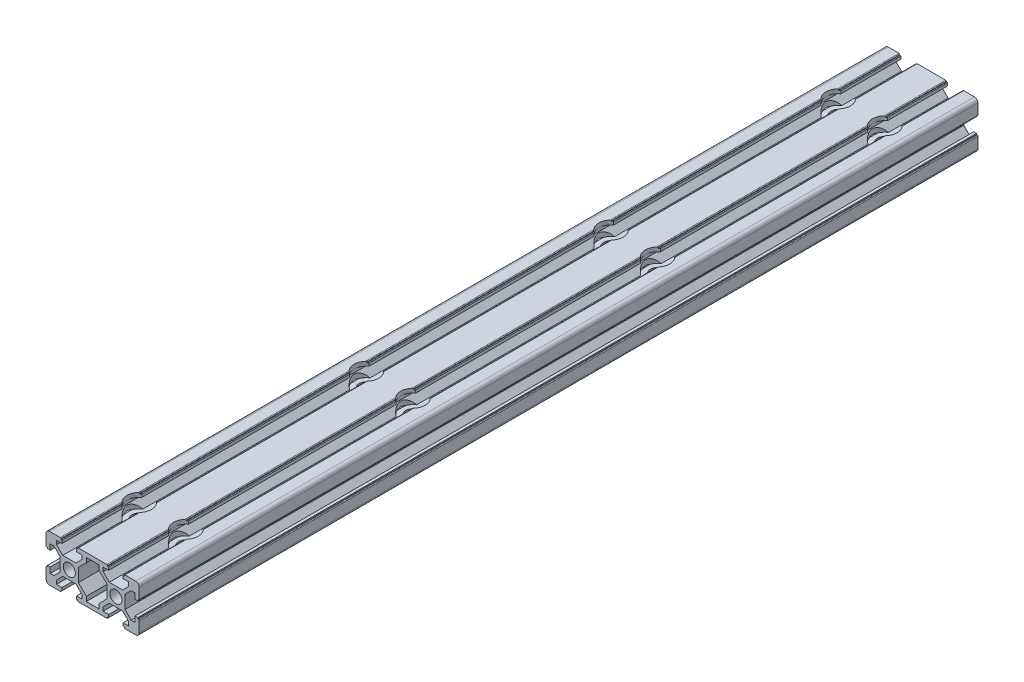
SolidWorks part; units mm, degrees
ref_plane "前视基准面" through (0, 0, 0) normal (0, 0, 1) x (1, 0, 0)
ref_plane "上视基准面" through (0, 0, 0) normal (0, 1, 0) x (1, 0, 0)
ref_plane "右视基准面" through (0, 0, 0) normal (1, 0, 0) x (0, 0, -1)
sketch "草图1" plane through (0, 0, 0) normal (0, 0, 1) x (1, 0, 0)
  line L0 (0, 0) -> (0, -41497.3383) construction
  line L1 (0, 0) -> (41497.3383, 0) construction
  line L2 (-13.9, 0) -> (-13.9, 2.8393)
  line L3 (-13.9, 2.8393) -> (-16.5607, 5.5)
  line L4 (-16.5607, 5.5) -> (-18.2, 5.5)
  line L5 (-18.2, 5.5) -> (-18.2, 3.1)
  line L6 (-18.2, 3.1) -> (-19.4, 3.1)
  line L7 (-19.4, 3.1) -> (-19.4, 3.6)
  line L8 (-19.4, 3.6) -> (-20, 3.6)
  line L9 (-20, 3.6) -> (-20, 10)
  line L10 (-20, 10) -> (-13.6, 10)
  line L11 (-13.6, 10) -> (-13.6, 9.4)
  line L12 (-13.6, 9.4) -> (-13.1, 9.4)
  line L13 (-13.1, 9.4) -> (-13.1, 8.2)
  line L14 (-13.1, 8.2) -> (-15.5, 8.2)
  line L15 (-15.5, 6.5607) -> (-12.8393, 3.9)
  line L16 (-12.8393, 3.9) -> (-7.1607, 3.9)
  line L17 (-4.5, 6.5607) -> (-7.1607, 3.9)
  line L18 (-4.5, 6.5607) -> (-4.5, 8.2)
  line L19 (-4.5, 8.2) -> (-6.9, 8.2)
  line L20 (-6.9, 8.2) -> (-6.9, 9.4)
  line L21 (-6.9, 9.4) -> (-6.4, 9.4)
  line L22 (-6.4, 9.4) -> (-6.4, 10)
  line L23 (-6.4, 10) -> (6.4, 10)
  line L24 (-15.5, 8.2) -> (-15.5, 6.5607)
  line L25 (-10, 0) -> (-20, 10) construction
  line L26 (-6.1, -2.8393) -> (-6.1, 2.8393)
  line L27 (-6.1, 2.8393) -> (-2.7, 6.2393)
  line L28 (-2.7, 6.2393) -> (-2.7, 8.2)
  line L29 (-2.7, 8.2) -> (2.7, 8.2)
  line L30 (-10, 0) -> (0, 10) construction
  line L31 (13.9, 0) -> (13.9, 2.8393)
  line L32 (6.1, -2.8393) -> (6.1, 2.8393)
  line L33 (4.5, 6.5607) -> (7.1607, 3.9)
  line L34 (12.8393, 3.9) -> (7.1607, 3.9)
  line L35 (6.1, 2.8393) -> (2.7, 6.2393)
  line L36 (2.7, 6.2393) -> (2.7, 8.2)
  line L37 (4.5, 6.5607) -> (4.5, 8.2)
  line L38 (6.4, 9.4) -> (6.4, 10)
  line L39 (6.9, 9.4) -> (6.4, 9.4)
  line L40 (6.9, 8.2) -> (6.9, 9.4)
  line L41 (4.5, 8.2) -> (6.9, 8.2)
  line L42 (13.1, 9.4) -> (13.1, 8.2)
  line L43 (13.6, 9.4) -> (13.1, 9.4)
  line L44 (13.6, 10) -> (13.6, 9.4)
  line L45 (20, 10) -> (13.6, 10)
  line L46 (20, 3.6) -> (20, 10)
  line L47 (19.4, 3.6) -> (20, 3.6)
  line L48 (19.4, 3.1) -> (19.4, 3.6)
  line L49 (18.2, 3.1) -> (19.4, 3.1)
  line L50 (18.2, 5.5) -> (18.2, 3.1)
  line L51 (16.5607, 5.5) -> (18.2, 5.5)
  line L52 (13.9, 2.8393) -> (16.5607, 5.5)
  line L53 (15.5, 6.5607) -> (12.8393, 3.9)
  line L54 (15.5, 8.2) -> (15.5, 6.5607)
  line L55 (13.1, 8.2) -> (15.5, 8.2)
  line L56 (15.5, -6.5607) -> (12.8393, -3.9)
  line L57 (13.9, -2.8393) -> (16.5607, -5.5)
  line L58 (16.5607, -5.5) -> (18.2, -5.5)
  line L59 (18.2, -5.5) -> (18.2, -3.1)
  line L60 (18.2, -3.1) -> (19.4, -3.1)
  line L61 (19.4, -3.1) -> (19.4, -3.6)
  line L62 (19.4, -3.6) -> (20, -3.6)
  line L63 (12.8393, -3.9) -> (7.1607, -3.9)
  line L64 (13.9, 0) -> (13.9, -2.8393)
  line L65 (13.1, -8.2) -> (15.5, -8.2)
  line L66 (15.5, -8.2) -> (15.5, -6.5607)
  line L67 (20, -3.6) -> (20, -10)
  line L68 (20, -10) -> (13.6, -10)
  line L69 (13.6, -10) -> (13.6, -9.4)
  line L70 (13.6, -9.4) -> (13.1, -9.4)
  line L71 (13.1, -9.4) -> (13.1, -8.2)
  line L72 (4.5, -8.2) -> (6.9, -8.2)
  line L73 (6.9, -8.2) -> (6.9, -9.4)
  line L74 (6.9, -9.4) -> (6.4, -9.4)
  line L75 (6.4, -9.4) -> (6.4, -10)
  line L76 (4.5, -6.5607) -> (4.5, -8.2)
  line L77 (2.7, -6.2393) -> (2.7, -8.2)
  line L78 (6.1, -2.8393) -> (2.7, -6.2393)
  line L79 (4.5, -6.5607) -> (7.1607, -3.9)
  line L80 (-2.7, -8.2) -> (2.7, -8.2)
  line L81 (-2.7, -6.2393) -> (-2.7, -8.2)
  line L82 (-6.1, -2.8393) -> (-2.7, -6.2393)
  line L83 (-4.5, -6.5607) -> (-7.1607, -3.9)
  line L84 (-4.5, -8.2) -> (-6.9, -8.2)
  line L85 (-4.5, -6.5607) -> (-4.5, -8.2)
  line L86 (-6.4, -10) -> (6.4, -10)
  line L87 (-6.4, -9.4) -> (-6.4, -10)
  line L88 (-6.9, -9.4) -> (-6.4, -9.4)
  line L89 (-6.9, -8.2) -> (-6.9, -9.4)
  line L90 (-13.1, -9.4) -> (-13.1, -8.2)
  line L91 (-13.6, -9.4) -> (-13.1, -9.4)
  line L92 (-13.6, -10) -> (-13.6, -9.4)
  line L93 (-15.5, -8.2) -> (-15.5, -6.5607)
  line L94 (-13.1, -8.2) -> (-15.5, -8.2)
  line L95 (-12.8393, -3.9) -> (-7.1607, -3.9)
  line L96 (-15.5, -6.5607) -> (-12.8393, -3.9)
  line L97 (-13.9, 0) -> (-13.9, -2.8393)
  line L98 (-13.9, -2.8393) -> (-16.5607, -5.5)
  line L99 (-19.4, -3.6) -> (-20, -3.6)
  line L100 (-19.4, -3.1) -> (-19.4, -3.6)
  line L101 (-18.2, -3.1) -> (-19.4, -3.1)
  line L102 (-18.2, -5.5) -> (-18.2, -3.1)
  line L103 (-16.5607, -5.5) -> (-18.2, -5.5)
  line L104 (-20, -3.6) -> (-20, -10)
  line L105 (-20, -10) -> (-13.6, -10)
  circle A0 centre (-10, 0) radius 2.6
  circle A1 centre (10, 0) radius 2.6
  point P50 (0, 8.2)
  point P95 (6.1, 0)
  point P96 (-6.1, 0)
  dimension "D1" = 5.2
  dimension "D2" = 45
  dimension "D3" = 1.5
  dimension "D4" = 20
  dimension "D5" = 40
  dimension "D6" = 0.75
  dimension "D7" = 7.2
  dimension "D8" = 6.2
  dimension "D9" = 6.1
  dimension "D10" = 1.8
  dimension "D11" = 1.2
  dimension "D12" = 12.2
  dimension "D13" = 5.4
  dimension "D14" = 11
  dimension "D15" = 1.5
  dimension "D16" = 0.75
extrude "凸台-拉伸1" add sketch "草图1" along normal mid plane 360
fillet "圆角1" radius 1.5 4 edges at (20, -10, 0) (20, 10, 0) (-20, -10, 0) (-20, 10, 0)
fillet "圆角2" radius 0.3 12 edges at (-6.4, 10, 0) (-13.6, 10, 0) (-20, 3.6, 0) (-20, -3.6, 0) (-13.6, -10, 0) (-6.4, -10, 0) (6.4, -10, 0) (20, -3.6, 0) (20, 3.6, 0) (13.6, -10, 0) (13.6, 10, 0) (6.4, 10, 0)
sketch "草图3" plane through (0, -3.9, 0) normal (0, -1, 0) x (1, 0, 0)
  line L0 (-10, -150) -> (10, -150) construction
  line L1 (-10, -52.5) -> (10, -52.5) construction
  line L2 (-6.1, -180) -> (6.1, -180) construction
  line L3 (0, 0) -> (-50000, 0) construction
  circle A0 centre (-10, -150) radius 3.1
  circle A1 centre (10, -150) radius 3.1
  circle A2 centre (10, 150) radius 3.1
  circle A3 centre (-10, 150) radius 3.1
  circle A4 centre (-10, -52.5) radius 3.1
  circle A5 centre (10, -52.5) radius 3.1
  circle A6 centre (10, 52.5) radius 3.1
  circle A7 centre (-10, 52.5) radius 3.1
  point P5 (0, -150)
  point P18 (0, -52.5)
  dimension "D1" = 6.2
  dimension "D2" = 20
  dimension "D4" = 52.5
  dimension "D3" = 30
extrude "切除-拉伸1" cut sketch "草图3" against normal through all both and the other way through all
sketch "草图4" plane through (0, 3.9, 0) normal (0, 1, 0) x (1, 0, 0)
  circle A0 centre (-10, -150) radius 5.25
  circle A1 centre (10, -150) radius 5.25
  circle A2 centre (-10, 150) radius 5.25
  circle A3 centre (10, 150) radius 5.25
  circle A4 centre (-10, 52.5) radius 5.25
  circle A5 centre (10, 52.5) radius 5.25
  circle A6 centre (-10, -52.5) radius 5.25
  circle A7 centre (10, -52.5) radius 5.25
  dimension "D1" = 10.5
extrude "切除-拉伸2" cut sketch "草图4" along normal through all
equation "\"D6@草图1\"=1/2*\"D3@草图1\""
equation "\"D16@草图1\"=0.5*\"D15@草图1\""
